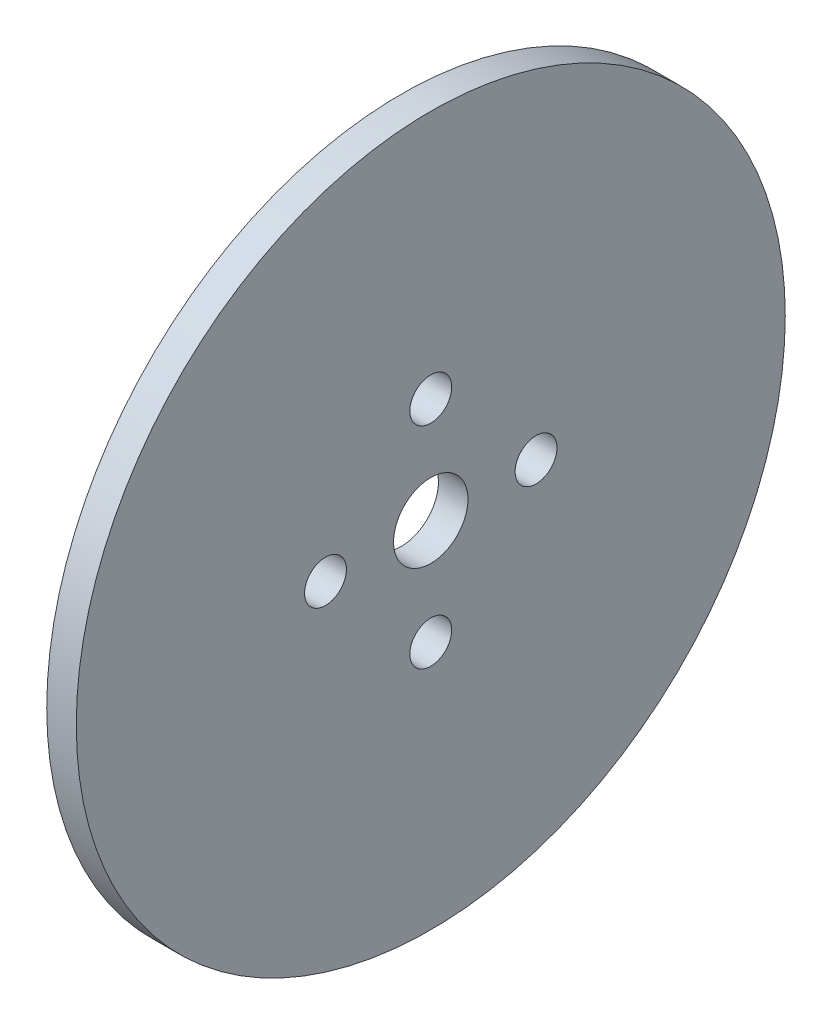
SolidWorks part; units mm, degrees
ref_plane "Front Plane" through (0, 0, 0) normal (1, 0, 0) x (0, 1, 0)
ref_plane "Top Plane" through (0, 0, 0) normal (0, 0, 1) x (0, 1, 0)
ref_plane "Right Plane" through (0, 0, 0) normal (0, 1, 0) x (-1, 0, 0)
sketch "Sketch1" plane through (0, 0, 0) normal (1, 0, 0) x (0, 1, 0)
  circle A0 centre (0, 0) radius 38.1
  circle A2 centre (0, 0) radius 4
  dimension "D1" = 76.2
  dimension "D2" = 8
extrude "Boss-Extrude2" add sketch "Sketch1" along normal blind 3.175
sketch "Sketch4" plane through (3.175, 0, 0) normal (1, 0, 0) x (0, 1, 0)
  line L0 (0, -11.3137) -> (-11.3137, 0) construction
  line L1 (0, -11.3137) -> (11.3137, 0) construction
  line L2 (-11.3137, 0) -> (0, 11.3137) construction
  line L3 (11.3137, 0) -> (0, 11.3137) construction
  line L4 (0, -11.3137) -> (0, 11.3137) construction
  line L5 (-11.3137, 0) -> (11.3137, 0) construction
  line L7 (-4, 19.3137) -> (4, 19.3137) construction
  line L8 (-4, 19.3137) -> (-4, 7.3137) construction
  line L9 (-4, 7.3137) -> (4, 7.3137) construction
  line L10 (4, 19.3137) -> (4, 7.3137) construction
  circle A0 centre (0, 11.3137) radius 2.25
  circle A1 centre (11.3137, 0) radius 2.25
  circle A2 centre (-11.3137, 0) radius 2.25
  circle A3 centre (0, -11.3137) radius 2.25
  circle A4 centre (0, 0) radius 20.574 construction
  circle A5 centre (0, 0) radius 8 construction
  circle A6 centre (0, 8) radius 2.25 construction
  point P1 (0, 0)
  point P14 (0, 19.3137)
  dimension "D2" = 4.5
  dimension "D6" = 41.148
  dimension "D7" = 16
  dimension "D1" = 16
  dimension "D3" = 8
  dimension "D4" = 12
  dimension "D5" = 8
extrude "Cut-Extrude3" cut sketch "Sketch4" against normal blind 30.394
